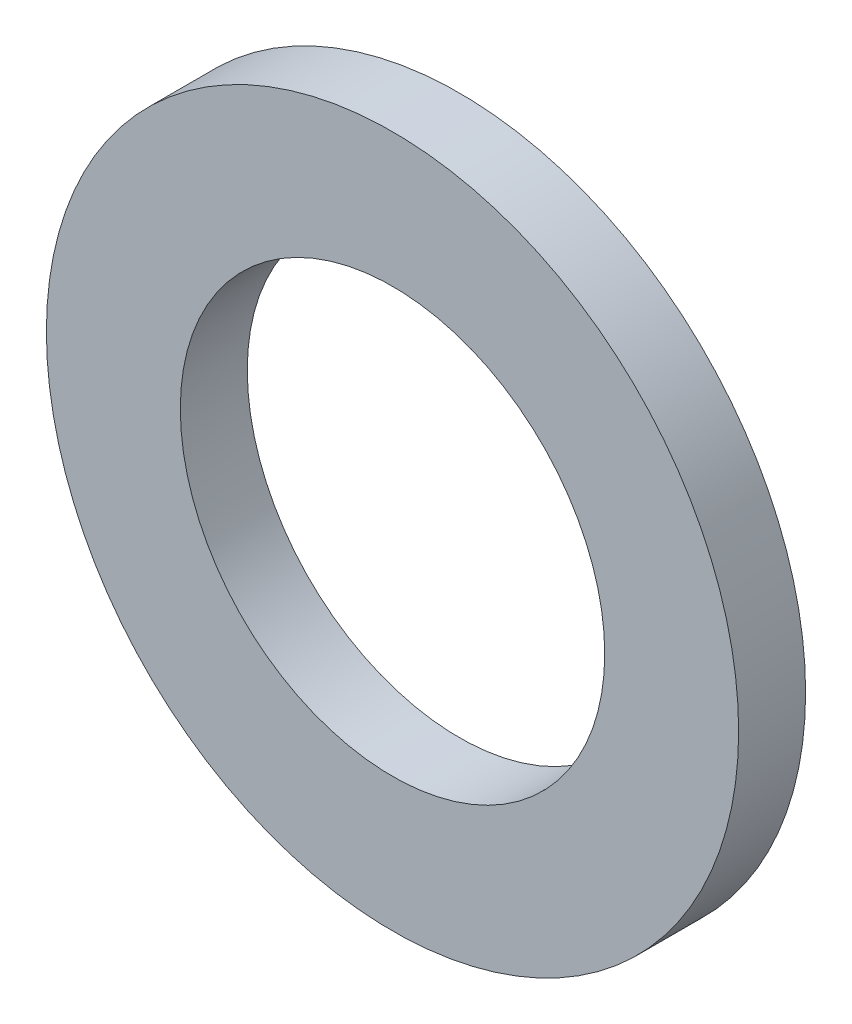
SolidWorks part; units mm, degrees
ref_plane "Front Plane" through (0, 0, 0) normal (0, 0, 1) x (1, 0, 0)
ref_plane "Top Plane" through (0, 0, 0) normal (0, 1, 0) x (1, 0, 0)
ref_plane "Right Plane" through (0, 0, 0) normal (1, 0, 0) x (0, 0, -1)
sketch "Sketch1" plane through (0, 0, 0) normal (0, 0, 1) x (1, 0, 0)
  circle A0 centre (0, 0) radius 4.025
  circle A1 centre (0, 0) radius 6.565
  dimension "D1" = 8.05
  dimension "D2" = 2.54
extrude "Boss-Extrude1" add sketch "Sketch1" along normal blind 1.27
move or copy body "Body-Move/Copy3" [suppressed] bodies to move or copy 101 parameters "D1"=0, "D2"=0, "D3"=0
move or copy body "Body-Move/Copy2" [suppressed] bodies to move or copy 101 parameters "D1"=0, "D2"=0, "D3"=0
move or copy body "Body-Move/Copy1" [suppressed] bodies to move or copy 104 parameters "D1"=0, "D2"=0, "D3"=0
